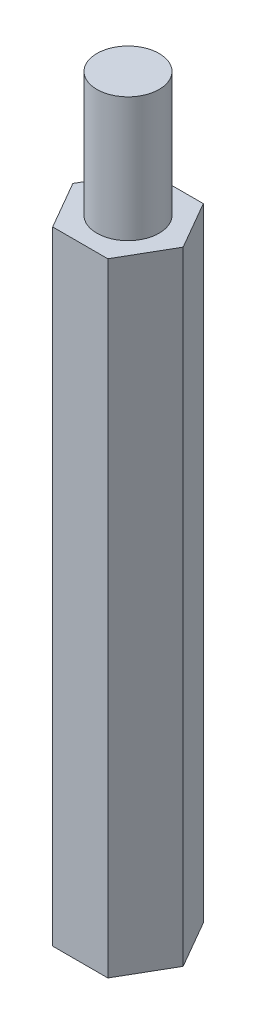
SolidWorks part; units mm, degrees
ref_plane "前视基准面" through (0, 0, 0) normal (0, 0, 1) x (1, 0, 0)
ref_plane "上视基准面" through (0, 0, 0) normal (0, 1, 0) x (1, 0, 0)
ref_plane "右视基准面" through (0, 0, 0) normal (1, 0, 0) x (0, 0, -1)
other "Configuration Table"
sketch "草图1" plane through (0, 0, 0) normal (0, 1, 0) x (1, 0, 0)
  line L1 (2.6558, 0) -> (1.3279, 2.3)
  line L2 (1.3279, 2.3) -> (-1.3279, 2.3)
  line L3 (-1.3279, 2.3) -> (-2.6558, 0)
  line L4 (-2.6558, 0) -> (-1.3279, -2.3)
  line L5 (-1.3279, -2.3) -> (1.3279, -2.3)
  line L6 (1.3279, -2.3) -> (2.6558, 0)
  circle A0 centre (0, 0) radius 2.3 construction
  dimension "D1" = 4.6
extrude "凸台-拉伸1" add sketch "草图1" along normal blind 30
sketch "草图2" plane through (0, 30, 0) normal (0, 1, 0) x (1, 0, 0)
  circle A0 centre (0, 0) radius 1.5
  dimension "D1" = 3
extrude "凸台-拉伸2" add sketch "草图2" along normal blind 6
cosmetic thread "装饰螺纹线2"
sketch "草图3" plane through (0, 0, 0) normal (0, -1, 0) x (1, 0, 0)
  circle A0 centre (0, 0) radius 1.5
  dimension "D1" = 3
extrude "切除-拉伸1" cut sketch "草图3" against normal blind 10
cosmetic thread "装饰螺纹线1" parameters "D2"=4
